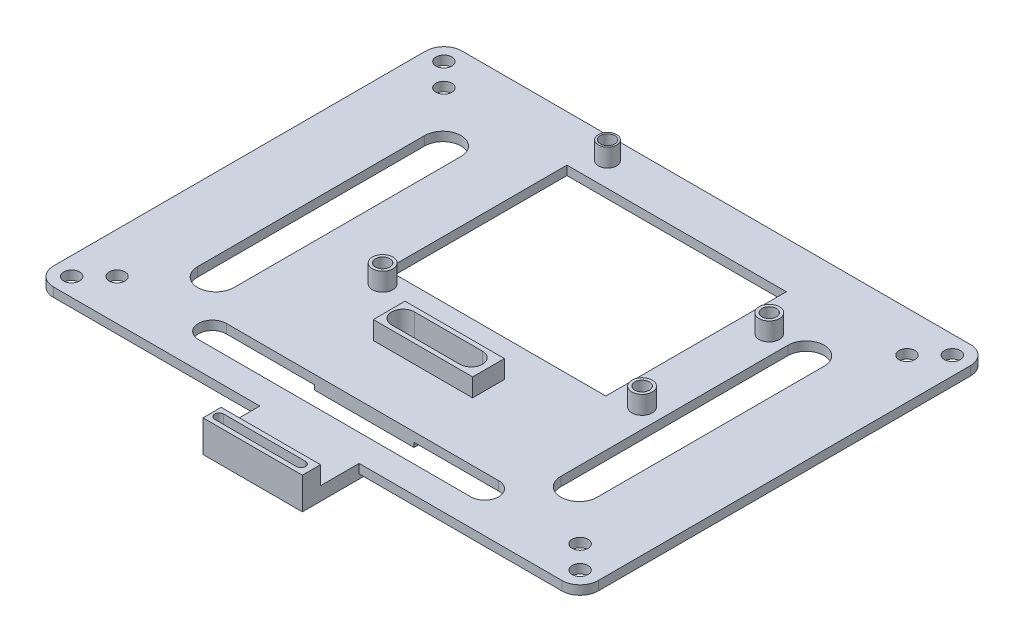
SolidWorks part; units mm, degrees
material "ABS"
ref_plane "Front Plane" through (0, 0, 0) normal (0, 0, 1) x (1, 0, 0)
ref_plane "Top Plane" through (0, 0, 0) normal (0, 1, 0) x (1, 0, 0)
ref_plane "Right Plane" through (0, 0, 0) normal (1, 0, 0) x (0, 0, -1)
sketch "Sketch1" plane through (0, 0, 0) normal (0, 1, 0) x (1, 0, 0)
  line L0 (0, 0) -> (0, 45) construction
  line L1 (-60, -45) -> (60, -45)
  line L2 (-60, -45) -> (-60, 45)
  line L3 (-60, 45) -> (60, 45)
  line L4 (60, -45) -> (60, 45)
  line L5 (-60, -45) -> (60, 45) construction
  line L6 (-60, 45) -> (60, -45) construction
  line L11 (-60, -13) -> (-29, 13) construction
  line L12 (-60, 13) -> (-29, -13) construction
  line L17 (-51.4342, -7.9248) -> (-37.3869, 8.1292) construction
  line L18 (-51.3868, 8.0751) -> (-37.5005, -8.0723) construction
  point P0 (0, 0)
  point P6 (-44.5, 0)
  point P12 (-60, 0)
  point P22 (0, 0)
  dimension "D1" = 31
  dimension "D2" = 26
  dimension "D3" = 15.5
  dimension "D5" = 14
  dimension "D6" = 16
  dimension "D13" = 120
  dimension "D14" = 90
extrude "Boss-Extrude1" add sketch "Sketch1" along normal blind 2
fillet "Fillet1" radius 4 4 edges at (60, 1, -45) (60, 1, 45) (-60, 1, 45) (-60, 1, -45)
sketch "Sketch3" plane through (0, 2, 0) normal (0, 1, 0) x (1, 0, 0)
  line L1 (-34.3, 42.7) -> (34.3, 42.7)
  line L2 (-34.3, 42.7) -> (-34.3, -10.7)
  line L3 (-34.3, -10.7) -> (34.3, -10.7)
  line L4 (34.3, 42.7) -> (34.3, -10.7)
  line L5 (-34.3, 42.7) -> (34.3, -10.7) construction
  line L6 (-34.3, -10.7) -> (34.3, 42.7) construction
  line L7 (-24.1806, -2.8228) -> (24.1806, -2.8228)
  line L8 (-24.1806, -2.8228) -> (-24.1806, 34.8228)
  line L9 (-24.1806, 34.8228) -> (24.1806, 34.8228)
  line L10 (24.1806, -2.8228) -> (24.1806, 34.8228)
  line L11 (-24.1806, -2.8228) -> (24.1806, 34.8228) construction
  line L12 (-24.1806, 34.8228) -> (24.1806, -2.8228) construction
  circle A0 centre (31.74, -3.08) radius 2.25
  circle A1 centre (-19.06, 40.1) radius 2
  circle A2 centre (31.74, 24.92) radius 2.25
  point P0 (0, 16)
  point P13 (0, 16)
  dimension "D5" = 4.5
  dimension "D6" = 4
  dimension "D9" = 4.5
  dimension "D1" = 68.6
  dimension "D2" = 53.4
  dimension "D3" = 16
  dimension "D4" = 7.62
  dimension "D7" = 15.24
  dimension "D8" = 50.8
  dimension "D10" = 50.8
  dimension "D11" = 17.78
extrude "Boss-Extrude2" add sketch "Sketch3" along normal blind 4 from surface at 0 separate body contours A1 | A2 | A0 starting at face at (0, 2, 0)
sketch "Sketch4" plane through (0, 6, 0) normal (0, 1, 0) x (1, 0, 0)
  circle A0 centre (-19.06, 40.1) radius 1.6
  circle A1 centre (31.74, 24.92) radius 1.6
  circle A2 centre (31.74, -3.08) radius 1.6
  dimension "D1" = 3.2
extrude "Cut-Extrude2" cut sketch "Sketch4" against normal blind 10
sketch "Sketch7" plane through (0, 2, 0) normal (0, 1, 0) x (1, 0, 0)
  line L1 (-22.6885, 25.6906) -> (20.6885, 25.6906)
  line L2 (-22.6885, 25.6906) -> (-22.6885, 4.3094)
  line L3 (-22.6885, 4.3094) -> (20.6885, 4.3094)
  line L4 (20.6885, 25.6906) -> (20.6885, 4.3094)
  line L5 (-22.6885, 25.6906) -> (20.6885, 4.3094) construction
  line L6 (-22.6885, 4.3094) -> (20.6885, 25.6906) construction
  point P0 (-1, 15)
  dimension "D1" = 1
  dimension "D2" = 15
extrude "Cut-Extrude3" cut sketch "Sketch7" against normal blind 10
sketch "Sketch9" plane through (0, 2, 0) normal (0, 1, 0) x (1, 0, 0)
  line L0 (-56, -45) -> (56, -45) construction
  line L1 (-60, -41) -> (-60, 41) construction
  circle A0 centre (-20.33, -8.16) radius 2.25
  dimension "D1" = 36.84
  dimension "D3" = 4.5
  dimension "D2" = 39.67
extrude "Boss-Extrude3" add sketch "Sketch9" along normal blind 4
sketch "Sketch10" plane through (0, 6, 0) normal (0, 1, 0) x (1, 0, 0)
  circle A0 centre (-20.33, -8.16) radius 1.6
extrude "Cut-Extrude4" cut sketch "Sketch10" against normal blind 8
sketch "Sketch11" plane through (0, 2, 0) normal (0, 1, 0) x (1, 0, 0)
  line L5 (-56, -45) -> (56, -45) construction
  line L6 (-10.5581, -13) -> (11.326, -13)
  line L7 (-10.5581, -13) -> (-10.5581, -20)
  line L8 (-10.5581, -20) -> (11.326, -20)
  line L9 (11.326, -13) -> (11.326, -20)
  dimension "D1" = 21.8841
  dimension "D2" = 32
  dimension "D3" = 7
extrude "Boss-Extrude4" add sketch "Sketch11" along normal blind 4
sketch "Sketch12" plane through (0, 2, 0) normal (0, 1, 0) x (1, 0, 0)
  line L1 (-10.5581, -13) -> (11.326, -13)
  line L2 (-10.5581, -13) -> (-10.5581, -57.5)
  line L3 (-10.5581, -57.5) -> (11.326, -57.5)
  line L4 (11.326, -13) -> (11.326, -57.5)
  dimension "D1" = 44.5
extrude "Boss-Extrude5" add sketch "Sketch12" against normal blind 3
sketch "Sketch13" plane through (0, 2, 0) normal (0, 1, 0) x (1, 0, 0)
  line L0 (11.326, -57.5) -> (11.326, -45) construction
  line L1 (-10.5581, -57.5) -> (11.326, -57.5)
  line L2 (-10.5581, -57.5) -> (-10.5581, -53.5)
  line L3 (-10.5581, -53.5) -> (11.326, -53.5)
  line L4 (11.326, -57.5) -> (11.326, -53.5)
  dimension "D1" = 4
extrude "Boss-Extrude6" add sketch "Sketch13" along normal blind 4
sketch "Sketch14" plane through (0, 6, 0) normal (0, 1, 0) x (1, 0, 0)
  line L0 (-7.5, -16.5) -> (7.5, -16.5) construction
  line L1 (-7.5, -14) -> (7.5, -14)
  line L2 (-7.5, -19) -> (7.5, -19)
  line L3 (11.326, -20) -> (11.326, -13) construction
  arc A0 (-7.5, -14) -> (-7.5, -19) centre (-7.5, -16.5) ccw
  arc A1 (7.5, -19) -> (7.5, -14) centre (7.5, -16.5) ccw
  point P2 (0, -16.5)
  point P10 (11.326, -16.5)
extrude "Cut-Extrude5" cut sketch "Sketch14" against normal blind 11
sketch "Sketch15" plane through (0, 6, 0) normal (0, 1, 0) x (1, 0, 0)
  line L0 (-9, -55.5) -> (9, -55.5) construction
  line L1 (-9, -54.5) -> (9, -54.5)
  line L2 (-9, -56.5) -> (9, -56.5)
  line L4 (-10.5581, -57.5) -> (11.326, -57.5) construction
  arc A0 (-9, -54.5) -> (-9, -56.5) centre (-9, -55.5) ccw
  arc A1 (9, -56.5) -> (9, -54.5) centre (9, -55.5) ccw
  point P2 (0, -55.5)
  dimension "D1" = 2
extrude "Cut-Extrude6" cut sketch "Sketch15" against normal blind 11
sketch "Sketch17" plane through (0, 2, 0) normal (0, 1, 0) x (1, 0, 0)
  line L0 (-60, -41) -> (-60, 41) construction
  line L1 (-56, 45) -> (56, 45) construction
  line L2 (0, -55) -> (0, 55) construction
  line L3 (-55, 0) -> (55, 0) construction
  circle A0 centre (-51, 36) radius 1.75
  circle A1 centre (51, 36) radius 1.75
  circle A2 centre (51, -36) radius 1.75
  circle A3 centre (-51, -36) radius 1.75
  dimension "D1" = 9
  dimension "D2" = 9
extrude "Cut-Extrude7" cut sketch "Sketch17" against normal blind 3
sketch "Sketch18" plane through (0, 2, 0) normal (0, 1, 0) x (1, 0, 0)
  line L0 (-56, 45) -> (56, 45) construction
  line L1 (-60, -41) -> (-60, 41) construction
  circle A0 centre (-56, 41) radius 1.75
  dimension "D3" = 3.5
  dimension "D1" = 4
  dimension "D2" = 4
extrude "Cut-Extrude8" cut sketch "Sketch18" against normal blind 10
mirror "Mirror1" about plane through (0, 0, 0) normal (1, 0, 0) of "Cut-Extrude8"
mirror "Mirror2" about plane through (0, 0, 0) normal (0, 0, 1) of "Mirror1", "Cut-Extrude8"
sketch "Sketch19" plane through (0, 2, 0) normal (0, 1, 0) x (1, 0, 0)
  line L0 (-40, -25.2331) -> (-40, 24.7669) construction
  line L1 (-44, -25.2331) -> (-44, 24.7669)
  line L2 (-36, -25.2331) -> (-36, 24.7669)
  line L3 (-60, -41) -> (-60, 41) construction
  arc A0 (-44, -25.2331) -> (-36, -25.2331) centre (-40, -25.2331) ccw
  arc A1 (-36, 24.7669) -> (-44, 24.7669) centre (-40, 24.7669) ccw
  point P2 (-40, -0.2331)
  dimension "D3" = 4
  dimension "D1" = 20
  dimension "D2" = 50
extrude "Cut-Extrude9" cut sketch "Sketch19" against normal blind 10
mirror "Mirror3" about plane through (0, 0, 0) normal (1, 0, 0) of "Cut-Extrude9"
sketch "Sketch20" plane through (0, 2, 0) normal (0, 1, 0) x (1, 0, 0)
  line L0 (-30, -36) -> (30, -36) construction
  line L1 (-30, -32.9249) -> (30, -32.9249)
  line L2 (-30, -39.0751) -> (30, -39.0751)
  arc A0 (-30, -32.9249) -> (-30, -39.0751) centre (-30, -36) ccw
  arc A1 (30, -39.0751) -> (30, -32.9249) centre (30, -36) ccw
  point P2 (0, -36)
  dimension "D1" = 60
extrude "Cut-Extrude10" cut sketch "Sketch20" against normal blind 10
sketch "Sketch21" plane through (0, 2, 0) normal (0, 1, 0) x (1, 0, 0)
  line L1 (-22.6885, 34.7885) -> (25.6398, 34.7885)
  line L2 (-22.6885, 34.7885) -> (-22.6885, -4.9795)
  line L3 (-22.6885, -4.9795) -> (25.6398, -4.9795)
  line L4 (25.6398, 34.7885) -> (25.6398, -4.9795)
extrude "Cut-Extrude11" cut sketch "Sketch21" against normal blind 10
